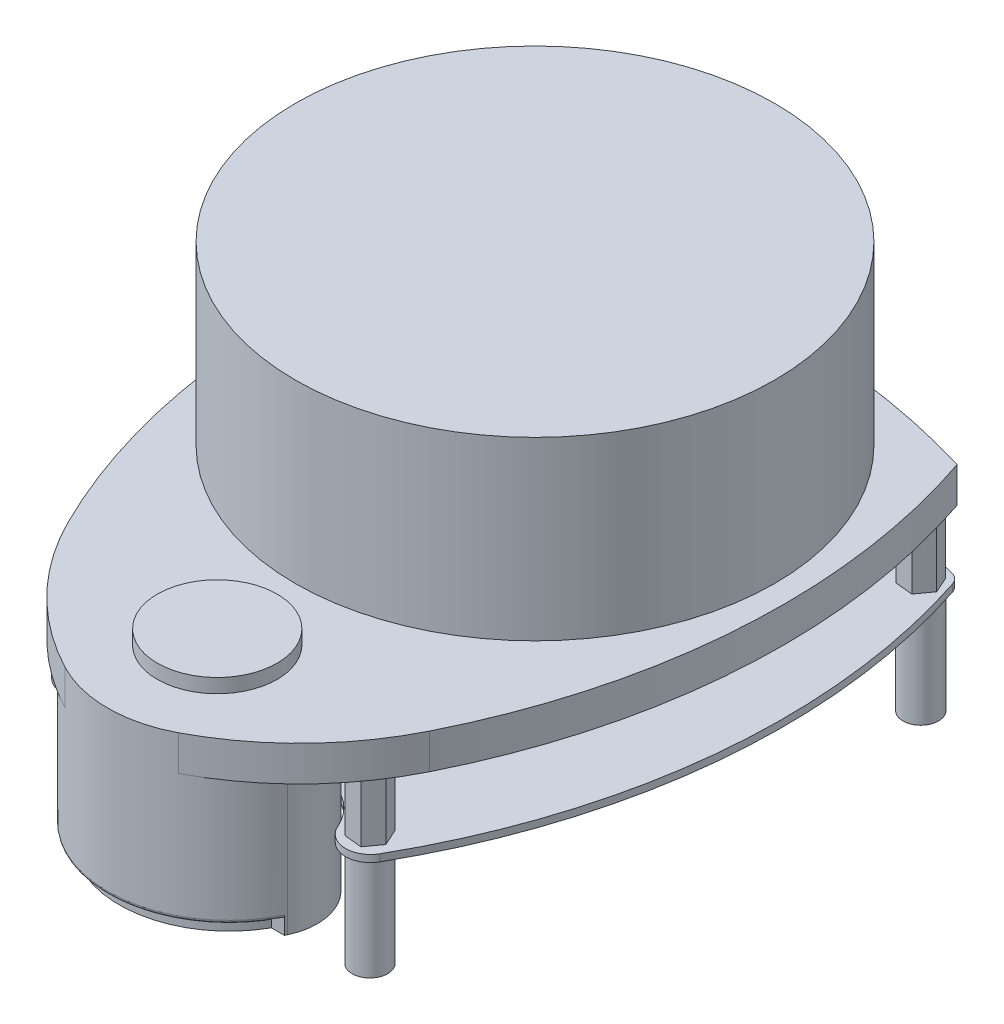
SolidWorks part; units mm, degrees
ref_plane "前视基准面" through (0, 0, 0) normal (0, 0, 1) x (1, 0, 0)
ref_plane "上视基准面" through (0, 0, 0) normal (0, 1, 0) x (1, 0, 0)
ref_plane "右视基准面" through (0, 0, 0) normal (1, 0, 0) x (0, 0, -1)
sketch "草图1" plane through (0, 0, 0) normal (0, 1, 0) x (1, 0, 0)
  line L0 (-0.5902, 98.9166) -> (218.0765, 98.9166) construction
  line L1 (-35, 49.25) -> (35, 49.25) construction
  line L2 (-35, 49.25) -> (-35, -49.25) construction
  line L3 (-35, -49.25) -> (35, -49.25) construction
  line L4 (35, 49.25) -> (35, -49.25) construction
  line L5 (-35, 49.25) -> (35, -49.25) construction
  line L6 (-35, -49.25) -> (35, 49.25) construction
  circle A0 centre (-28.3878, 41.1754) radius 1.2067
  circle A1 centre (-28.3878, 41.1754) radius 2.5254
  circle A2 centre (27.7186, 41.1754) radius 1.2067
  circle A3 centre (27.7186, 41.1754) radius 2.5254
  circle A4 centre (19.6955, -28.9464) radius 1.2067
  circle A5 centre (19.6955, -28.9464) radius 2.5254
  circle A6 centre (-20.3846, -29.0064) radius 1.2067
  circle A7 centre (-20.3846, -29.0064) radius 2.5254
  point P0 (0, 0)
  dimension "D1" = 70
  dimension "D2" = 98.5
extrude "凸台-拉伸1" add sketch "草图1" along normal blind 15
sketch "草图2" plane through (0, 15, 0) normal (0, 1, 0) x (1, 0, 0)
  line L0 (-28.3878, 41.1754) -> (27.7186, 41.1754) construction
  line L1 (-0.594, 98.81) -> (218.0727, 98.81) construction
  line L3 (-0.2714, -28.5276) -> (-0.2714, 119.672) construction
  line L4 (-0.2714, -28.5276) -> (-0.2714, -52.7962) construction
  arc A0 (-0.2714, 48.4281) -> (-29.591, 44.2957) centre (-0.3496, -57.0963) ccw
  arc A1 (-30.9374, 42.9968) -> (-29.591, 44.2957) centre (-29.0368, 42.374) cw
  arc A2 (-30.9374, 42.9968) -> (-23.4609, -30.7624) centre (55.9066, 14.5411) ccw
  arc A3 (13.0394, -26.3513) -> (16.5889, -30.4087) centre (8.5178, -33.8882) cw
  arc A4 (-23.4609, -30.7624) -> (-17.1318, -30.4087) centre (-20.3846, -29.0064) ccw
  arc A5 (-13.5822, -26.3513) -> (-17.1318, -30.4087) centre (-9.0606, -33.8882) ccw
  arc A6 (13.0394, -26.3513) -> (-13.5822, -26.3513) centre (-0.2714, -48.5388) ccw
  arc A7 (22.9181, -30.7624) -> (16.5889, -30.4087) centre (19.8418, -29.0064) cw
  arc A8 (30.3946, 42.9968) -> (22.9181, -30.7624) centre (-56.4495, 14.5411) cw
  arc A9 (30.3946, 42.9968) -> (29.0482, 44.2957) centre (28.494, 42.374) ccw
  arc A10 (-0.2714, 48.4281) -> (29.0482, 44.2957) centre (-0.1932, -57.0963) cw
  dimension "D1" = 2
extrude "凸台-拉伸2" add sketch "草图2" along normal blind 1
sketch "草图3" plane through (0, 16, 0) normal (0, 1, 0) x (1, 0, 0)
  line L0 (22.2077, -29.2043) -> (21.1749, -26.8997)
  line L1 (-18.9051, -26.9596) -> (-21.4174, -26.7018)
  line L2 (-21.4174, -26.7018) -> (-22.8968, -28.7485)
  line L3 (-22.8968, -28.7485) -> (-21.864, -31.0531)
  line L4 (-21.864, -31.0531) -> (-19.3517, -31.311)
  line L5 (-19.3517, -31.311) -> (-17.8723, -29.2642)
  line L6 (-17.8723, -29.2642) -> (-18.9051, -26.9596)
  line L7 (21.1749, -26.8997) -> (18.6627, -26.6418)
  line L8 (18.2161, -30.9932) -> (20.7283, -31.251)
  line L9 (18.6627, -26.6418) -> (17.1833, -28.6886)
  line L10 (20.7283, -31.251) -> (22.2077, -29.2043)
  line L11 (17.1833, -28.6886) -> (18.2161, -30.9932)
  line L12 (26.6858, 43.48) -> (25.2064, 41.4332)
  line L13 (29.1981, 43.2221) -> (26.6858, 43.48)
  line L14 (30.2309, 40.9175) -> (29.1981, 43.2221)
  line L15 (26.2392, 39.1286) -> (28.7515, 38.8708)
  line L16 (25.2064, 41.4332) -> (26.2392, 39.1286)
  line L17 (28.7515, 38.8708) -> (30.2309, 40.9175)
  line L18 (-30.9, 41.4332) -> (-29.8672, 39.1286)
  line L19 (-29.8672, 39.1286) -> (-27.355, 38.8708)
  line L20 (-27.355, 38.8708) -> (-25.8755, 40.9175)
  line L21 (-25.8755, 40.9175) -> (-26.9083, 43.2221)
  line L22 (-29.4206, 43.48) -> (-30.9, 41.4332)
  line L23 (-26.9083, 43.2221) -> (-29.4206, 43.48)
  circle A0 centre (-20.3846, -29.0064) radius 2.1871 construction
  circle A1 centre (-20.3846, -29.0064) radius 1.2067
  circle A2 centre (19.6955, -28.9464) radius 1.2067
  circle A3 centre (19.6955, -28.9464) radius 2.1871 construction
  circle A4 centre (27.7186, 41.1754) radius 2.1871 construction
  circle A5 centre (27.7186, 41.1754) radius 1.2067
  circle A6 centre (-28.3878, 41.1754) radius 2.1871 construction
  circle A7 centre (-28.3878, 41.1754) radius 1.2067
extrude "凸台-拉伸3" add sketch "草图3" along normal blind 9
sketch "草图4" plane through (0, 25, 0) normal (0, 1, 0) x (1, 0, 0)
  line L0 (-0.2714, 54.5495) -> (-0.2714, -48.5388) construction
  arc A0 (-0.2714, 48.428) -> (-30.5938, 44.0006) centre (-0.3506, -57.079) ccw
  arc A1 (-30.5938, 44.0006) -> (-25.9106, -26.1696) centre (55.8613, 14.5293) ccw
  arc A2 (-8.3012, -44.1893) -> (7.7584, -44.1893) centre (-0.2714, -28.9464) ccw
  arc A3 (-25.9106, -26.1696) -> (-8.3012, -44.1893) centre (10.8224, -7.8871) ccw
  arc A4 (25.3678, -26.1696) -> (7.7584, -44.1893) centre (-11.3652, -7.8871) cw
  arc A5 (30.051, 44.0006) -> (25.3678, -26.1696) centre (-56.4041, 14.5293) cw
  arc A6 (-0.2714, 48.428) -> (30.051, 44.0006) centre (-0.1922, -57.079) cw
extrude "凸台-拉伸4" add sketch "草图4" along normal blind 5
sketch "草图5" plane through (0, 25, 0) normal (0, -1, 0) x (1, 0, 0)
  line L0 (-0.2714, 51.4406) -> (-0.2714, 18.9109) construction
  arc A0 (15.3235, 36.2693) -> (-15.8663, 36.2693) centre (-0.2714, 28.9464) ccw
  arc A1 (-15.8663, 36.2693) -> (-12.2856, 25.6232) centre (-8.5141, 32.8169) ccw
  arc A2 (-12.2856, 25.6232) -> (11.7428, 25.6232) centre (-0.2714, 48.5388) ccw
  arc A3 (15.3235, 36.2693) -> (11.7428, 25.6232) centre (7.9713, 32.8169) cw
extrude "凸台-拉伸5" add sketch "草图5" along normal blind 20
sketch "草图6" plane through (0, 5, 0) normal (0, -1, 0) x (1, 0, 0)
  line L0 (-15.7242, 36.5646) -> (-13.8706, 36.5646)
  line L1 (13.3277, 36.5646) -> (15.1814, 36.5646)
  arc A0 (15.1814, 36.5646) -> (-15.7242, 36.5646) centre (-0.2714, 28.9464) ccw
  arc A1 (13.3277, 36.5646) -> (-13.8706, 36.5646) centre (-0.2714, 28.9464) ccw
extrude "切除-拉伸1" cut sketch "草图6" against normal blind 2
fillet "圆角1" radius 0.5 1 edges at (-0.2714, 7, 46.175)
sketch "草图7" plane through (0, 30, 0) normal (0, 1, 0) x (1, 0, 0)
  line L0 (-0.2714, 48.428) -> (-0.2714, -46.175) construction
  line L1 (-30.5938, 44.0006) -> (30.051, 44.0006) construction
  line L2 (0.5749, 82.4974) -> (219.2416, 82.4974) construction
  arc A0 (-8.3012, -44.1893) -> (7.7584, -44.1893) centre (-0.2714, -28.9464) ccw construction
  circle A1 centre (-0.2714, 14.4382) radius 14.6018
  circle A2 centre (-0.2714, -30.637) radius 8.493
extrude "凸台-拉伸6" add sketch "草图7" along normal blind 2
sketch "草图8" plane through (0, 32, 0) normal (0, 1, 0) x (1, 0, 0)
  circle A0 centre (-0.2714, 14.4382) radius 34
  dimension "D1" = 68
extrude "凸台-拉伸7" add sketch "草图8" along normal blind 25
